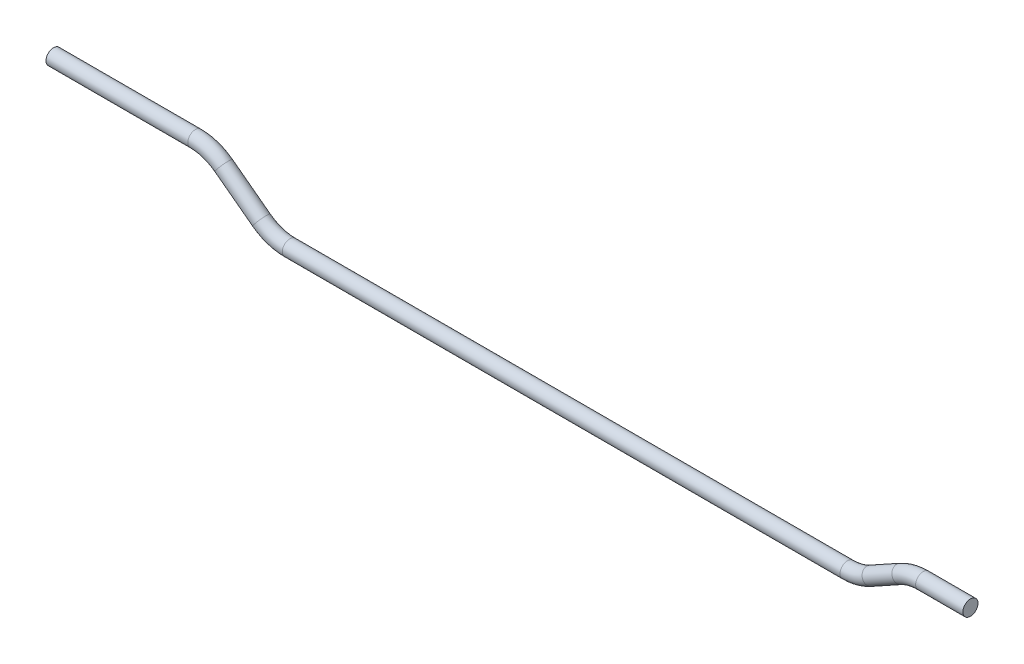
SolidWorks part; units mm, degrees
ref_plane "Front Plane" through (0, 0, 0) normal (0, 0, 1) x (1, 0, 0)
ref_plane "Top Plane" through (0, 0, 0) normal (0, 1, 0) x (1, 0, 0)
ref_plane "Right Plane" through (0, 0, 0) normal (1, 0, 0) x (0, 0, -1)
sketch "Sketch1" plane through (0, 0, 0) normal (1, 0, 0) x (0, 0, -1)
  circle A0 centre (0, 0) radius 0.8
  dimension "D1" = 1.6
sketch "Sketch2" plane through (0, 0, 0) normal (0, 0, 1) x (1, 0, 0)
  line L0 (0, 0) -> (15, 0)
  line L1 (0, -0.8) -> (0, 0.8) construction
  line L2 (18, -1) -> (22, -4)
  line L3 (25, -5) -> (84, -5)
  line L4 (86.4231, -4.3736) -> (89.5769, -2.6264)
  line L5 (92, -2) -> (97, -2)
  arc A0 (22, -4) -> (25, -5) centre (25, 0) ccw
  arc A1 (15, 0) -> (18, -1) centre (15, -5) cw
  arc A2 (89.5769, -2.6264) -> (92, -2) centre (92, -7) cw
  arc A3 (86.4231, -4.3736) -> (84, -5) centre (84, 0) cw
  dimension "D3" = 5
  dimension "D5" = 5
  dimension "D1" = 97
  dimension "D2" = 5
  dimension "D4" = 3
  dimension "D6" = 10
  dimension "D7" = 15
  dimension "D8" = 8
  dimension "D9" = 5
sweep "Sweep1" add profiles "Sketch1" path "Sketch2"
